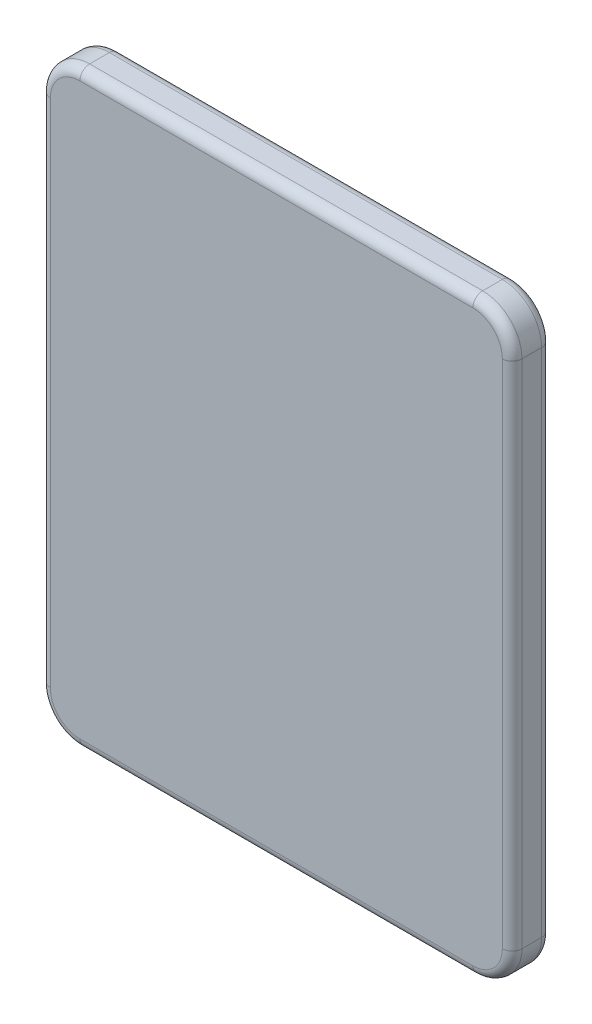
SolidWorks part; units mm, degrees
ref_plane "Front Plane" through (0, 0, 0) normal (0, 0, 1) x (1, 0, 0)
ref_plane "Top Plane" through (0, 0, 0) normal (0, 1, 0) x (1, 0, 0)
ref_plane "Right Plane" through (0, 0, 0) normal (1, 0, 0) x (0, 0, -1)
sketch "Sketch1" plane through (0, 0, 0) normal (0, 0, 1) x (1, 0, 0)
  line L1 (600, -750) -> (-600, -750)
  line L2 (600, -750) -> (600, 750)
  line L3 (600, 750) -> (-600, 750)
  line L4 (-600, -750) -> (-600, 750)
  line L5 (600, -750) -> (-600, 750) construction
  line L6 (600, 750) -> (-600, -750) construction
  point P0 (0, 0)
  dimension "D1" = 1200
  dimension "D2" = 1500
extrude "Boss-Extrude1" add sketch "Sketch1" along normal blind 100
fillet "Fillet1" radius 100 4 edges at (-600, -750, 50) (600, -750, 50) (600, 750, 50) (-600, 750, 50)
fillet "Fillet2" radius 25 16 edges at (570.7107, -720.7107, 0) (600, 0, 0) (570.7107, 720.7107, 0) (0, 750, 0) (-570.7107, 720.7107, 0) (-600, 0, 0) (-570.7107, -720.7107, 0) (0, -750, 0) (-570.7107, 720.7107, 100) (0, 750, 100) (570.7107, 720.7107, 100) (600, 0, 100) (570.7107, -720.7107, 100) (0, -750, 100) (-570.7107, -720.7107, 100) (-600, 0, 100)
